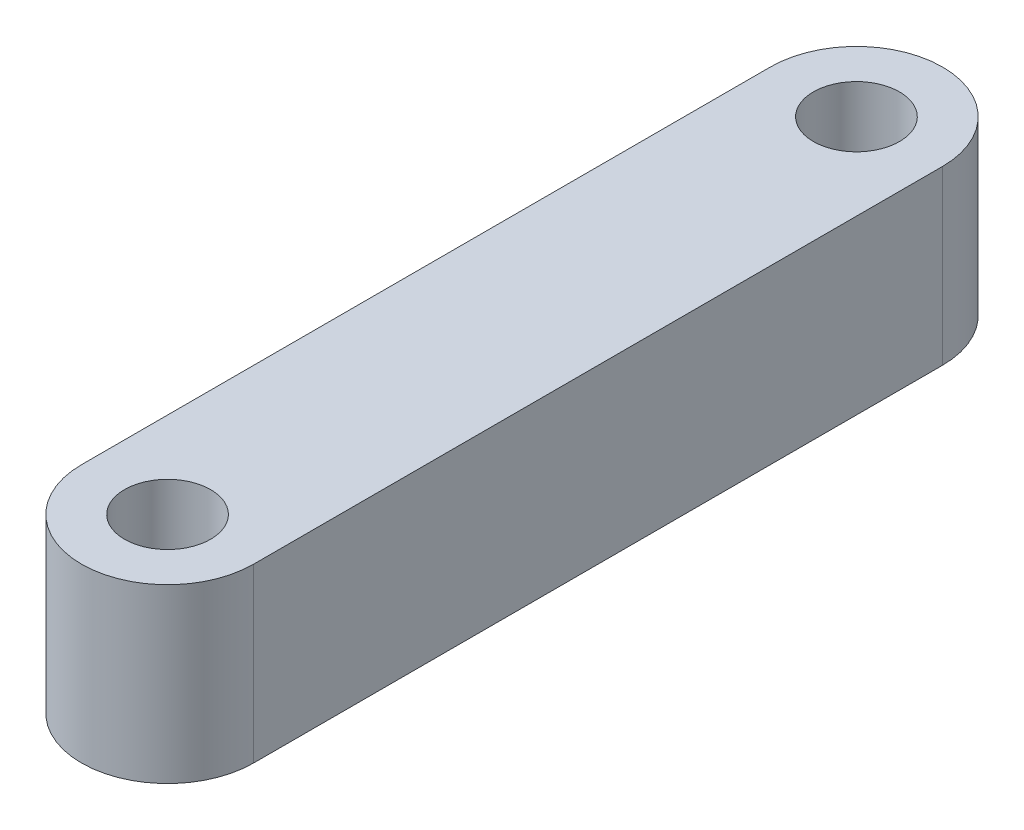
SolidWorks part; units mm, degrees
material "PLA"
ref_plane "Front Plane" through (0, 0, 0) normal (0, 0, 1) x (1, 0, 0)
ref_plane "Top Plane" through (0, 0, 0) normal (0, 1, 0) x (1, 0, 0)
ref_plane "Right Plane" through (0, 0, 0) normal (1, 0, 0) x (0, 0, -1)
sketch "Sketch1" plane through (0, 0, 0) normal (0, 1, 0) x (1, 0, 0)
  line L0 (-3.175, 25.4) -> (-3.175, 0)
  line L1 (3.175, 25.4) -> (3.175, 0)
  circle A0 centre (0, 0) radius 1.5875
  arc A1 (-3.175, 0) -> (3.175, 0) centre (0, 0) ccw
  circle A4 centre (0, 25.4) radius 1.5875
  arc A5 (3.175, 25.4) -> (-3.175, 25.4) centre (0, 25.4) ccw
  dimension "D2" = 6.35
  dimension "D3" = 3.175
  dimension "D1" = 25.4
  dimension "D4" = 6.35
extrude "Boss-Extrude1" add sketch "Sketch1" along normal blind 6.35
